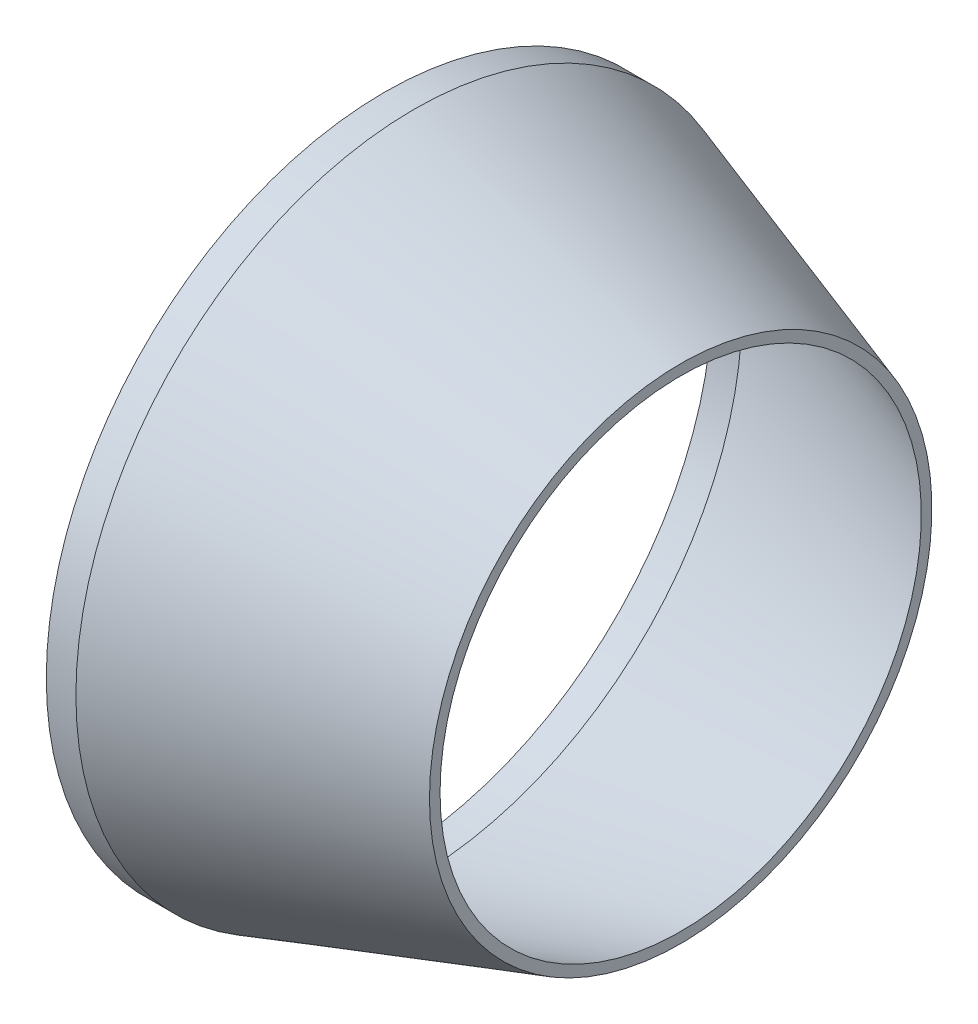
SolidWorks part; units mm, degrees
ref_plane "Front Plane" through (0, 0, 0) normal (0, 0, 1) x (1, 0, 0)
ref_plane "Top Plane" through (0, 0, 0) normal (0, 1, 0) x (1, 0, 0)
ref_plane "Right Plane" through (0, 0, 0) normal (1, 0, 0) x (0, 0, -1)
sketch "Sketch1" plane through (0, 0, 0) normal (0, 0, 1) x (1, 0, 0)
  line L0 (0, 0) -> (0, 50.8)
  line L1 (0, 50.8) -> (4.445, 50.8)
  line L3 (44.45, 0) -> (44.45, 37.719)
  line L4 (4.445, 50.8) -> (44.45, 37.719)
  line L5 (0, 0) -> (44.45, 0)
  dimension "D1" = 44.45
  dimension "D2" = 50.8
  dimension "D3" = 4.445
  dimension "D4" = 37.719
revolve "Revolve1" add sketch "Sketch1" angle 360 about L5
sketch "Sketch5" plane through (0, 0, 0) normal (0, 0, 1) x (1, 0, 0)
  line L0 (0, 0) -> (0, 49.2125)
  line L1 (0, 50.8) -> (0, -50.8) construction
  line L2 (0, 49.2125) -> (4.445, 49.2125)
  line L3 (4.445, 50.8) -> (4.445, -50.8) construction
  line L4 (0, 0) -> (44.45, 0)
  line L5 (44.45, -37.719) -> (44.45, 37.719) construction
  line L6 (44.45, 0) -> (44.45, 36.1315)
  line L7 (44.45, 36.1315) -> (4.445, 49.2125)
  dimension "D1" = 36.1315
  dimension "D2" = 49.2125
revolve "Cut-Revolve2" cut sketch "Sketch5" angle 360 about L4
